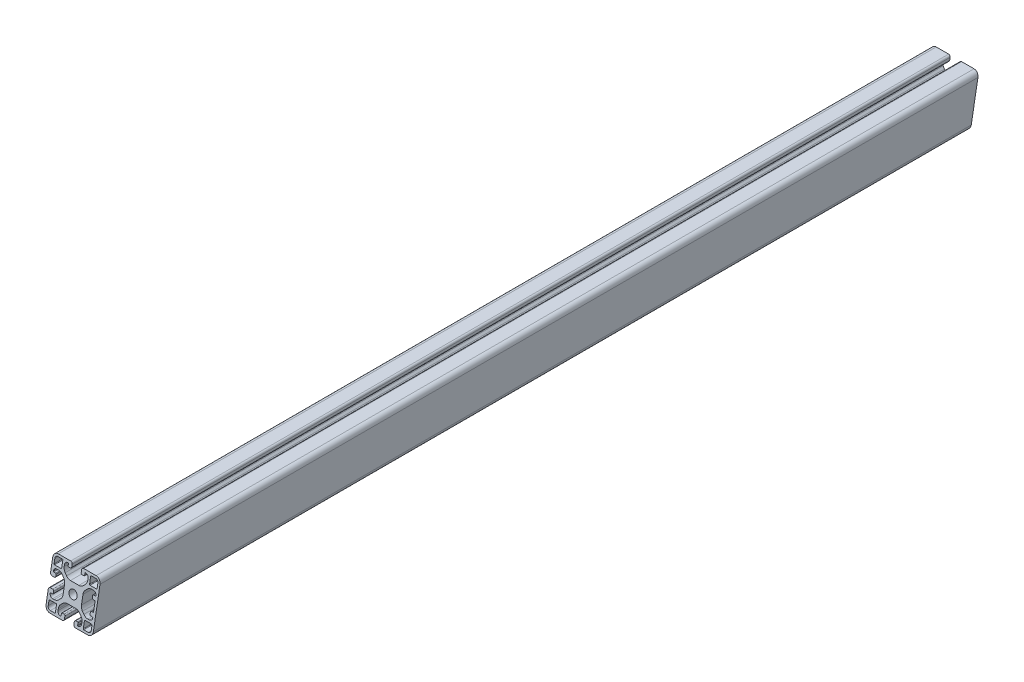
SolidWorks part; units mm, degrees
ref_plane "Piano frontale" through (0, 0, 0) normal (0, 0, 1) x (1, 0, 0)
ref_plane "Piano superiore" through (0, 0, 0) normal (0, 1, 0) x (1, 0, 0)
ref_plane "Piano destro" through (0, 0, 0) normal (1, 0, 0) x (0, 0, -1)
ref_plane "Piano1" through (0, 0, -340) normal (0, 0, -1) x (-1, 0, 0)
sketch "Schizzo1" plane through (0, 0, -340) normal (0, 0, -1) x (-1, 0, 0)
  line L0 (-12.3, -18.2) -> (-16, -18.2)
  line L1 (-18.2, -16) -> (-18.2, -12.3)
  line L2 (-17.7, -11.8) -> (-12.3, -11.8)
  line L3 (-11.8, -12.3) -> (-11.8, -17.7)
  line L4 (-11.8, 17.7) -> (-11.8, 12.3)
  line L5 (-12.3, 11.8) -> (-17.7, 11.8)
  line L6 (-18.2, 12.3) -> (-18.2, 16)
  line L7 (-16, 18.2) -> (-12.3, 18.2)
  line L8 (18.2, 16) -> (18.2, 12.3)
  line L9 (17.7, 11.8) -> (12.3, 11.8)
  line L10 (11.8, 12.3) -> (11.8, 17.7)
  line L11 (12.3, 18.2) -> (16, 18.2)
  line L12 (6.5, -15.5) -> (5, -15.5)
  line L13 (4, -16.5) -> (4, -18.5)
  line L14 (5.5, -20) -> (16, -20)
  line L15 (20, -16) -> (20, -5.5)
  line L16 (18.5, -4) -> (16.5, -4)
  line L17 (15.5, -5) -> (15.5, -6.5)
  line L18 (16, -7) -> (17.55, -7)
  line L19 (18, -7.45) -> (18, -7.5)
  line L20 (15.5, -10) -> (14.1924, -10)
  line L21 (10.6569, -8.5355) -> (9.2145, -7.0931)
  line L22 (7.75, -3.5576) -> (7.75, 3.5576)
  line L23 (9.2145, 7.0931) -> (10.6569, 8.5355)
  line L24 (14.1924, 10) -> (15.5, 10)
  line L25 (18, 7.5) -> (18, 7.45)
  line L26 (17.55, 7) -> (16, 7)
  line L27 (15.5, 6.5) -> (15.5, 5)
  line L28 (16.5, 4) -> (18.5, 4)
  line L29 (20, 5.5) -> (20, 16)
  line L30 (16, 20) -> (5.5, 20)
  line L31 (4, 18.5) -> (4, 16.5)
  line L32 (5, 15.5) -> (6.5, 15.5)
  line L33 (7, 16) -> (7, 17.55)
  line L34 (7.45, 18) -> (7.5, 18)
  line L35 (10, 15.5) -> (10, 14.1924)
  line L36 (8.5355, 10.6569) -> (7.0931, 9.2145)
  line L37 (3.5576, 7.75) -> (-3.5576, 7.75)
  line L38 (-7.0931, 9.2145) -> (-8.5355, 10.6569)
  line L39 (-10, 14.1924) -> (-10, 15.5)
  line L40 (-7.5, 18) -> (-7.45, 18)
  line L41 (-7, 17.55) -> (-7, 16)
  line L42 (-6.5, 15.5) -> (-5, 15.5)
  line L43 (-4, 16.5) -> (-4, 18.5)
  line L44 (-5.5, 20) -> (-16, 20)
  line L45 (-20, 16) -> (-20, -16)
  line L46 (-16, -20) -> (-5.5, -20)
  line L47 (-4, -18.5) -> (-4, -16.5)
  line L48 (-5, -15.5) -> (-6.5, -15.5)
  line L49 (-7, -16) -> (-7, -17.55)
  line L50 (-7.45, -18) -> (-7.5, -18)
  line L51 (-10, -15.5) -> (-10, -14.1924)
  line L52 (-8.5355, -10.6569) -> (-7.0931, -9.2145)
  line L53 (-3.5576, -7.75) -> (3.5576, -7.75)
  line L54 (7.0931, -9.2145) -> (8.5355, -10.6569)
  line L55 (10, -14.1924) -> (10, -15.5)
  line L56 (7.5, -18) -> (7.45, -18)
  line L57 (7, -17.55) -> (7, -16)
  line L58 (18.2, -12.3) -> (18.2, -16)
  line L59 (16, -18.2) -> (12.3, -18.2)
  line L60 (11.8, -17.7) -> (11.8, -12.3)
  line L61 (12.3, -11.8) -> (17.7, -11.8)
  line L62 (-16, 7) -> (-17.5, 7)
  line L63 (-15.5, 10) -> (-14.1924, 10)
  line L64 (-10.6569, 8.5355) -> (-9.2145, 7.0931)
  line L65 (-7.75, 3.5576) -> (-7.75, -3.5576)
  line L66 (-9.2145, -7.0931) -> (-10.6569, -8.5355)
  line L67 (-14.1924, -10) -> (-15.5, -10)
  line L68 (-17.5, -7) -> (-16, -7)
  line L69 (-15.5, -6.5) -> (-15.5, -5)
  line L70 (-16.5, -4) -> (-17.5, -4)
  line L71 (-18, -3.5) -> (-18, 3.5)
  line L72 (-17.5, 4) -> (-16.5, 4)
  line L73 (-15.5, 5) -> (-15.5, 6.5)
  arc A0 (-16, -18.2) -> (-18.2, -16) centre (-16, -16) cw
  arc A1 (-18.2, -12.3) -> (-17.7, -11.8) centre (-17.7, -12.3) cw
  arc A2 (-12.3, -11.8) -> (-11.8, -12.3) centre (-12.3, -12.3) cw
  arc A3 (-11.8, -17.7) -> (-12.3, -18.2) centre (-12.3, -17.7) cw
  arc A4 (-12.3, 18.2) -> (-11.8, 17.7) centre (-12.3, 17.7) cw
  arc A5 (-11.8, 12.3) -> (-12.3, 11.8) centre (-12.3, 12.3) cw
  arc A6 (-17.7, 11.8) -> (-18.2, 12.3) centre (-17.7, 12.3) cw
  arc A7 (-18.2, 16) -> (-16, 18.2) centre (-16, 16) cw
  arc A8 (16, 18.2) -> (18.2, 16) centre (16, 16) cw
  arc A9 (18.2, 12.3) -> (17.7, 11.8) centre (17.7, 12.3) cw
  arc A10 (12.3, 11.8) -> (11.8, 12.3) centre (12.3, 12.3) cw
  arc A11 (11.8, 17.7) -> (12.3, 18.2) centre (12.3, 17.7) cw
  arc A12 (5, -15.5) -> (4, -16.5) centre (5, -16.5) ccw
  arc A13 (4, -18.5) -> (5.5, -20) centre (5.5, -18.5) ccw
  arc A14 (16, -20) -> (20, -16) centre (16, -16) ccw
  arc A15 (20, -5.5) -> (18.5, -4) centre (18.5, -5.5) ccw
  arc A16 (16.5, -4) -> (15.5, -5) centre (16.5, -5) ccw
  arc A17 (15.5, -6.5) -> (16, -7) centre (16, -6.5) ccw
  arc A18 (17.55, -7) -> (18, -7.45) centre (17.55, -7.45) cw
  arc A19 (18, -7.5) -> (15.5, -10) centre (15.5, -7.5) cw
  arc A20 (14.1924, -10) -> (10.6569, -8.5355) centre (14.1924, -5) cw
  arc A21 (9.2145, -7.0931) -> (7.75, -3.5576) centre (12.75, -3.5576) cw
  arc A22 (7.75, 3.5576) -> (9.2145, 7.0931) centre (12.75, 3.5576) cw
  arc A23 (10.6569, 8.5355) -> (14.1924, 10) centre (14.1924, 5) cw
  arc A24 (15.5, 10) -> (18, 7.5) centre (15.5, 7.5) cw
  arc A25 (18, 7.45) -> (17.55, 7) centre (17.55, 7.45) cw
  arc A26 (16, 7) -> (15.5, 6.5) centre (16, 6.5) ccw
  arc A27 (15.5, 5) -> (16.5, 4) centre (16.5, 5) ccw
  arc A28 (18.5, 4) -> (20, 5.5) centre (18.5, 5.5) ccw
  arc A29 (20, 16) -> (16, 20) centre (16, 16) ccw
  arc A30 (5.5, 20) -> (4, 18.5) centre (5.5, 18.5) ccw
  arc A31 (4, 16.5) -> (5, 15.5) centre (5, 16.5) ccw
  arc A32 (6.5, 15.5) -> (7, 16) centre (6.5, 16) ccw
  arc A33 (7, 17.55) -> (7.45, 18) centre (7.45, 17.55) cw
  arc A34 (7.5, 18) -> (10, 15.5) centre (7.5, 15.5) cw
  arc A35 (10, 14.1924) -> (8.5355, 10.6569) centre (5, 14.1924) cw
  arc A36 (7.0931, 9.2145) -> (3.5576, 7.75) centre (3.5576, 12.75) cw
  arc A37 (-3.5576, 7.75) -> (-7.0931, 9.2145) centre (-3.5576, 12.75) cw
  arc A38 (-8.5355, 10.6569) -> (-10, 14.1924) centre (-5, 14.1924) cw
  arc A39 (-10, 15.5) -> (-7.5, 18) centre (-7.5, 15.5) cw
  arc A40 (-7.45, 18) -> (-7, 17.55) centre (-7.45, 17.55) cw
  arc A41 (-7, 16) -> (-6.5, 15.5) centre (-6.5, 16) ccw
  arc A42 (-5, 15.5) -> (-4, 16.5) centre (-5, 16.5) ccw
  arc A43 (-4, 18.5) -> (-5.5, 20) centre (-5.5, 18.5) ccw
  arc A44 (-16, 20) -> (-20, 16) centre (-16, 16) ccw
  arc A45 (-20, -16) -> (-16, -20) centre (-16, -16) ccw
  arc A46 (-5.5, -20) -> (-4, -18.5) centre (-5.5, -18.5) ccw
  arc A47 (-4, -16.5) -> (-5, -15.5) centre (-5, -16.5) ccw
  arc A48 (-6.5, -15.5) -> (-7, -16) centre (-6.5, -16) ccw
  arc A49 (-7, -17.55) -> (-7.45, -18) centre (-7.45, -17.55) cw
  arc A50 (-7.5, -18) -> (-10, -15.5) centre (-7.5, -15.5) cw
  arc A51 (-10, -14.1924) -> (-8.5355, -10.6569) centre (-5, -14.1924) cw
  arc A52 (-7.0931, -9.2145) -> (-3.5576, -7.75) centre (-3.5576, -12.75) cw
  arc A53 (3.5576, -7.75) -> (7.0931, -9.2145) centre (3.5576, -12.75) cw
  arc A54 (8.5355, -10.6569) -> (10, -14.1924) centre (5, -14.1924) cw
  arc A55 (10, -15.5) -> (7.5, -18) centre (7.5, -15.5) cw
  arc A56 (7.45, -18) -> (7, -17.55) centre (7.45, -17.55) cw
  arc A57 (7, -16) -> (6.5, -15.5) centre (6.5, -16) ccw
  arc A58 (17.7, -11.8) -> (18.2, -12.3) centre (17.7, -12.3) cw
  arc A59 (18.2, -16) -> (16, -18.2) centre (16, -16) cw
  arc A60 (12.3, -18.2) -> (11.8, -17.7) centre (12.3, -17.7) cw
  arc A61 (11.8, -12.3) -> (12.3, -11.8) centre (12.3, -12.3) cw
  circle A62 centre (0, 0) radius 3.4
  arc A63 (-15.5, 6.5) -> (-16, 7) centre (-16, 6.5) ccw
  arc A64 (-17.5, 7) -> (-18, 7.5) centre (-17.5, 7.5) cw
  arc A65 (-18, 7.5) -> (-15.5, 10) centre (-15.5, 7.5) cw
  arc A66 (-14.1924, 10) -> (-10.6569, 8.5355) centre (-14.1924, 5) cw
  arc A67 (-9.2145, 7.0931) -> (-7.75, 3.5576) centre (-12.75, 3.5576) cw
  arc A68 (-7.75, -3.5576) -> (-9.2145, -7.0931) centre (-12.75, -3.5576) cw
  arc A69 (-10.6569, -8.5355) -> (-14.1924, -10) centre (-14.1924, -5) cw
  arc A70 (-15.5, -10) -> (-18, -7.5) centre (-15.5, -7.5) cw
  arc A71 (-18, -7.5) -> (-17.5, -7) centre (-17.5, -7.5) cw
  arc A72 (-16, -7) -> (-15.5, -6.5) centre (-16, -6.5) ccw
  arc A73 (-15.5, -5) -> (-16.5, -4) centre (-16.5, -5) ccw
  arc A74 (-17.5, -4) -> (-18, -3.5) centre (-17.5, -3.5) cw
  arc A75 (-18, 3.5) -> (-17.5, 4) centre (-17.5, 3.5) cw
  arc A76 (-16.5, 4) -> (-15.5, 5) centre (-16.5, 5) ccw
extrude "Estrusione-Estrusione1" add sketch "Schizzo1" against normal blind 750
sketch "Schizzo9" plane through (20, 0, 0) normal (1, 0, 0) x (0, 0, -1)
  line L0 (340, -16) -> (340, 16) construction
  line L1 (-410, 16) -> (-410, -16) construction
  line L2 (340, 16) -> (340, 20) construction
  line L3 (340, 20) -> (-410, 20) construction
  line L4 (-410, 20) -> (-410, 16) construction
  line L5 (340, -20) -> (340, -16) construction
  line L6 (-410, -16) -> (-410, -20) construction
  line L7 (-410, -20) -> (340, -20) construction
  line L8 (340, -16) -> (340, 16)
  line L9 (-410, 16) -> (-410, -16)
  line L10 (340, 16) -> (340, 20)
  line L11 (340, 20) -> (-410, 20)
  line L12 (-410, 20) -> (-410, 16)
  line L13 (340, -20) -> (340, -16)
  line L14 (-410, -16) -> (-410, -20)
  line L15 (-410, -20) -> (340, -20)
  line L16 (340, 20) -> (332.9469, -20)
  line L17 (-410, -20) -> (-402.9463, 20)
extrude "Taglio-Estrusione4" cut sketch "Schizzo9" against normal through all
